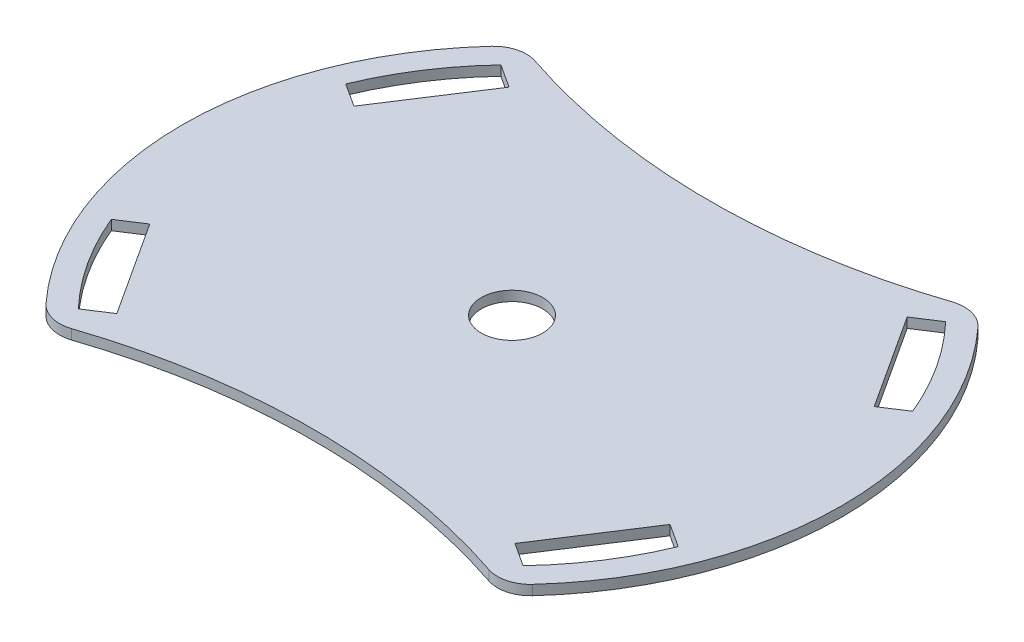
SolidWorks part; units mm, degrees
ref_plane "Plano frontal" through (0, 0, 0) normal (0, 0, 1) x (1, 0, 0)
ref_plane "Plano superior" through (0, 0, 0) normal (0, 1, 0) x (1, 0, 0)
ref_plane "Plano direito" through (0, 0, 0) normal (1, 0, 0) x (0, 0, -1)
sketch "Esboço1" plane through (0, 0, 0) normal (0, 1, 0) x (1, 0, 0)
  line L0 (0, 0) -> (0, 303.4641) construction
  line L1 (-180.7753, 0) -> (210.2784, 0) construction
  circle A0 centre (0, 0) radius 100
  circle A1 centre (0, 260) radius 200
  circle A2 centre (0, -260) radius 200
  circle A3 centre (0, 0) radius 9.3273
  point P6 (0, 60)
  point P7 (0, 100)
  dimension "D1" = 200
  dimension "D2" = 400
  dimension "D3" = 40
extrude "Ressalto-extrusão1" add sketch "Esboço1" along normal blind 3 contours A0 A2 A1
sketch "Esboço2" plane through (0, 3, 0) normal (0, 1, 0) x (1, 0, 0)
  line L0 (0, 0) -> (88.958, 57.77) construction
  line L1 (0, 0) -> (31.4415, -48.4157) construction
  line L2 (78.8685, 30.9476) -> (87.2552, 36.394)
  line L3 (78.8685, 30.9476) -> (60.3508, 59.4624)
  line L4 (60.3508, 59.4624) -> (68.7375, 64.9088)
  line L5 (87.2552, 36.394) -> (68.7375, 64.9088)
  line L6 (78.8685, 30.9476) -> (68.7375, 64.9088) construction
  line L7 (60.3508, 59.4624) -> (87.2552, 36.394) construction
  line L14 (0, -70.9431) -> (0, 83.1972) construction
  circle A0 centre (0, 0) radius 93
  point P2 (73.803, 47.9282)
  dimension "D1" = 83
  dimension "D2" = 10
  dimension "D3" = 90
  dimension "D4" = 34
  dimension "D5" = 90
extrude "Corte-extrusão1" cut sketch "Esboço2" against normal through all contours L2 A0 L4 L3
fillet "Filete1" radius 10 4 edges at (-69.0768, 1.5, -72.3077) (69.0768, 1.5, -72.3077) (69.0768, 1.5, 72.3077) (-69.0768, 1.5, 72.3077)
mirror "Espelhar1" about plane through (0, 0, 0) normal (1, 0, 0) of "Corte-extrusão1"
mirror "Espelhar2" about plane through (0, 0, 0) normal (0, 0, 1) of "Espelhar1", "Corte-extrusão1"
